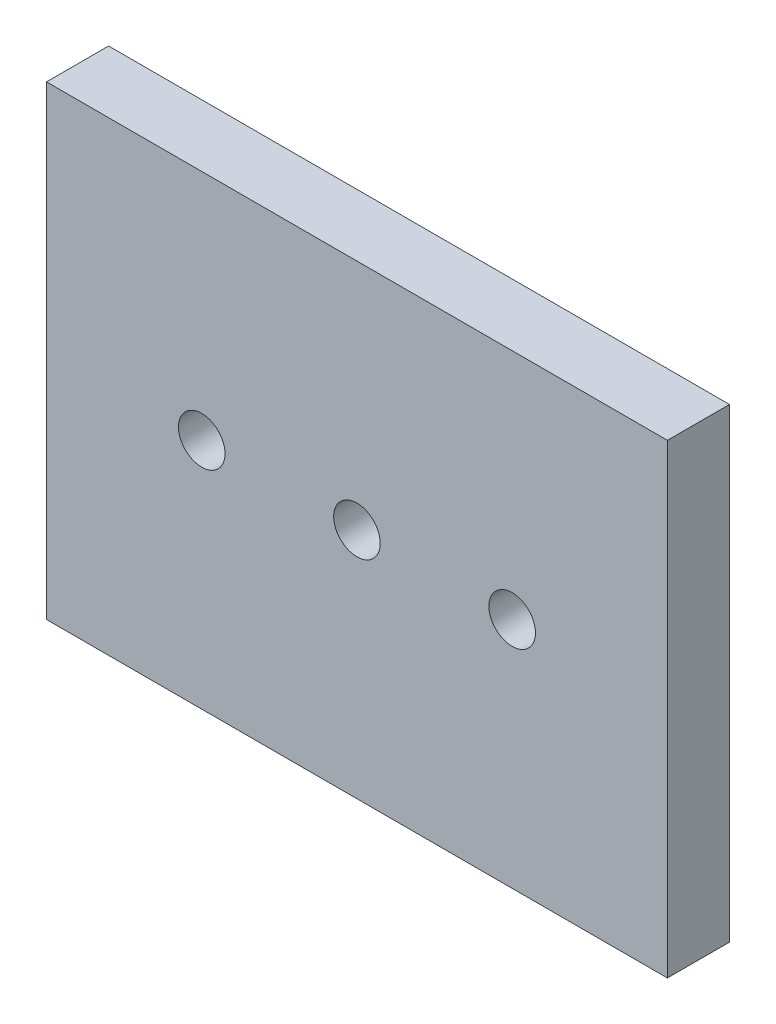
SolidWorks part; units mm, degrees
ref_plane "Plano frontal" through (0, 0, 0) normal (0, 0, 1) x (1, 0, 0)
ref_plane "Plano superior" through (0, 0, 0) normal (0, 1, 0) x (1, 0, 0)
ref_plane "Plano direito" through (0, 0, 0) normal (1, 0, 0) x (0, 0, -1)
sketch "Esboço1" plane through (0, 0, 0) normal (0, 0, 1) x (1, 0, 0)
  line L0 (20, 15) -> (-20, -15) construction
  line L1 (-20, 15) -> (20, 15)
  line L2 (-20, 15) -> (-20, -15)
  line L3 (-20, -15) -> (20, -15)
  line L4 (20, 15) -> (20, -15)
  dimension "D1" = 30
  dimension "D2" = 40
extrude "Ressalto-extrusão1" add sketch "Esboço1" along normal blind 4
sketch "Esboço2" plane through (0, 0, 4) normal (0, 0, 1) x (1, 0, 0)
  line L0 (-20, 0) -> (20, 0) construction
  line L1 (-20, 15) -> (-20, -15) construction
  line L2 (20, -15) -> (20, 15) construction
  circle A0 centre (0, 0) radius 1.5
  circle A1 centre (-10, 0) radius 1.5
  circle A2 centre (10, 0) radius 1.5
  dimension "D3" = 3
  dimension "D4" = 3
  dimension "D5" = 3
  dimension "D1" = 10
  dimension "D2" = 10
extrude "Corte-extrusão1" cut sketch "Esboço2" against normal up to next
